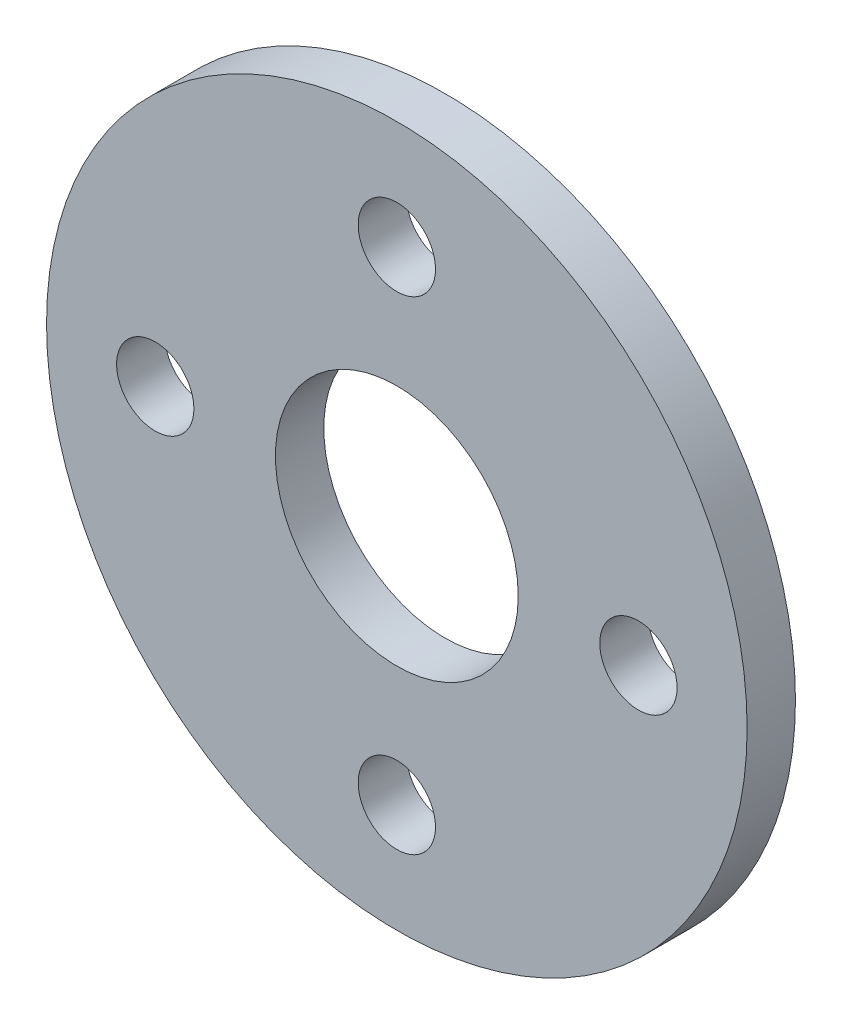
SolidWorks part; units mm, degrees
material "5052-O"
ref_plane "正面" through (0, 0, 0) normal (0, 0, 1) x (1, 0, 0)
ref_plane "平面" through (0, 0, 0) normal (0, 1, 0) x (1, 0, 0)
ref_plane "右側面" through (0, 0, 0) normal (1, 0, 0) x (0, 0, -1)
sketch "ｽｹｯﾁ1" plane through (0, 0, 0) normal (0, 0, 1) x (1, 0, 0)
  line L0 (0, 10) -> (0, 0) construction
  line L1 (10, 0) -> (0, 0) construction
  line L2 (0, -10) -> (0, 0) construction
  line L3 (-10, 0) -> (0, 0) construction
  circle A0 centre (0, 0) radius 14.5
  circle A1 centre (0, 10) radius 1.6
  circle A2 centre (0, 0) radius 5.025
  circle A3 centre (10, 0) radius 1.6
  circle A4 centre (0, -10) radius 1.6
  circle A5 centre (-10, 0) radius 1.6
  point P14 (0, 0)
  dimension "D1" = 3.2
  dimension "D3" = 10.05
  dimension "D5" = 29
  dimension "D2" = 10
  dimension "D4" = 4
extrude "ﾎﾞｽ - 押し出し1" add sketch "ｽｹｯﾁ1" along normal blind 2
